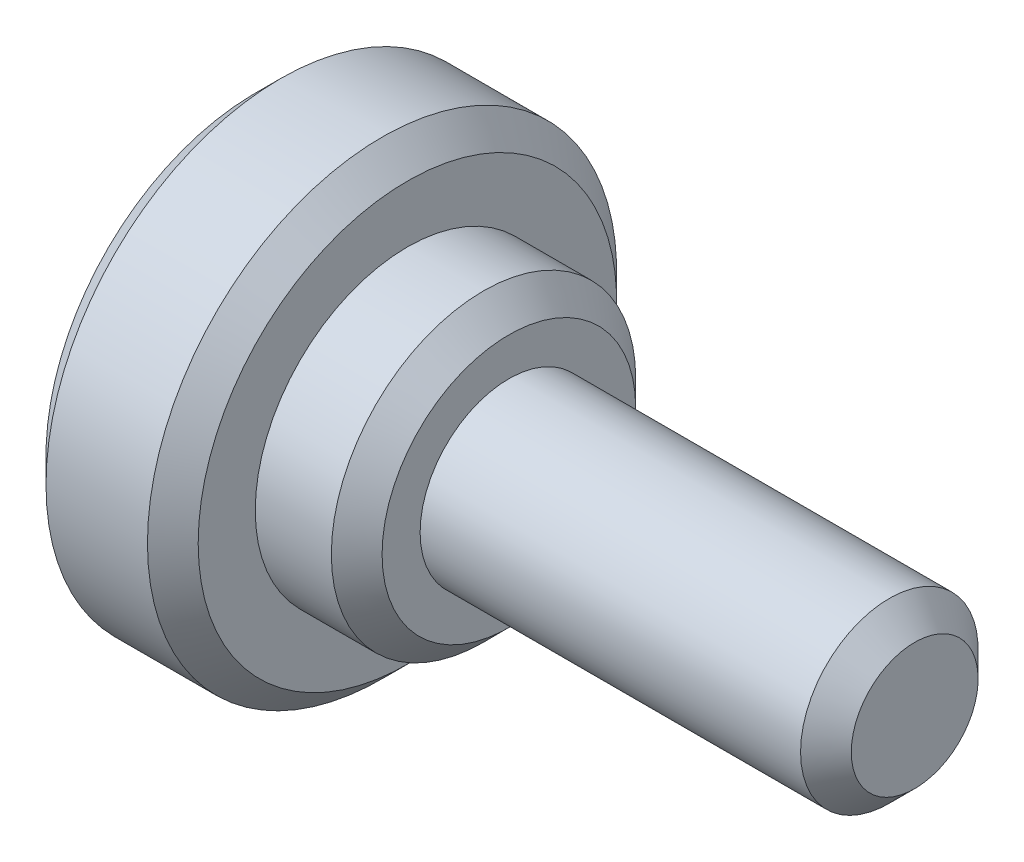
SolidWorks part; units mm, degrees
ref_plane "Спереди" through (0, 0, 0) normal (0, 0, 1) x (1, 0, 0)
ref_plane "Сверху" through (0, 0, 0) normal (0, 1, 0) x (1, 0, 0)
ref_plane "Справа" through (0, 0, 0) normal (1, 0, 0) x (0, 0, -1)
sketch "Эскиз1" plane through (0, 0, 0) normal (0, 0, 1) x (1, 0, 0)
  line L0 (0, 0) -> (27.21, 0) construction
  line L1 (1.5, 8.25) -> (4, 8.25)
  line L2 (4, 8.25) -> (4, 2.5)
  line L3 (4, 2.5) -> (6, 2.5)
  line L4 (6, 2.5) -> (7.4434, 0)
  line L6 (0, 9.25) -> (6, 9.25)
  line L7 (7.4434, 0) -> (26, 0)
  line L8 (6, 9.25) -> (6, 6)
  line L9 (6, 6) -> (10, 6)
  line L10 (0, 9.25) -> (0, 7)
  line L11 (10, 6) -> (10, 3.5)
  line L12 (10, 3.5) -> (26, 3.5)
  line L13 (0, 7) -> (1.5, 7)
  line L14 (26, 3.5) -> (26, 0)
  line L15 (1.5, 7) -> (1.5, 8.25)
  dimension "D1" = 18.5
  dimension "D2" = 16.5
  dimension "D3" = 4
  dimension "D4" = 6
  dimension "D5" = 20
  dimension "D6" = 16
  dimension "D7" = 12
  dimension "D8" = 5
  dimension "D9" = 6
  dimension "D10" = 60
  dimension "D11" = 7
  dimension "D12" = 2.5
  dimension "D13" = 14
revolve "Повернуть1" add sketch "Эскиз1" angle 360 about L0
chamfer "Фаска1" distance 1 angle 45 4 edges at (26, 0, 3.5) (10, 0, 6) (6, 0, 9.25) (0, 0, 9.25)
